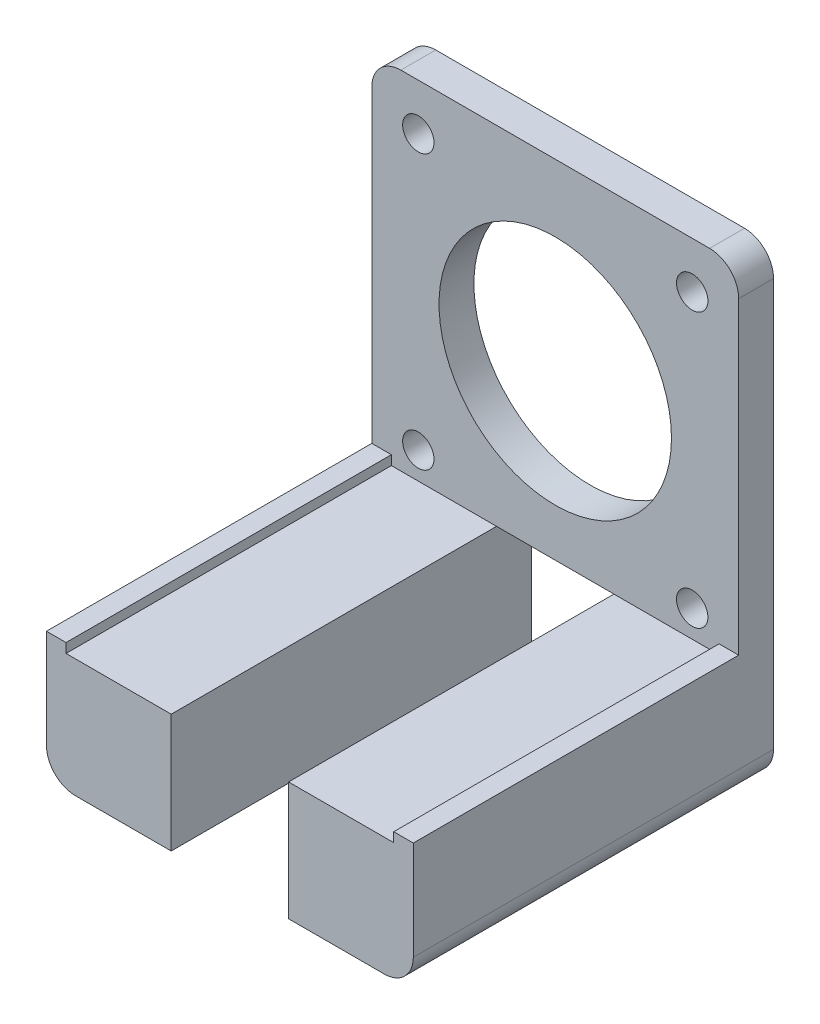
SolidWorks part; units mm, degrees
ref_plane "Alzado" through (0, 0, 0) normal (0, 0, 1) x (1, 0, 0)
ref_plane "Planta" through (0, 0, 0) normal (0, 1, 0) x (1, 0, 0)
ref_plane "Vista lateral" through (0, 0, 0) normal (1, 0, 0) x (0, 0, -1)
sketch "Croquis1" plane through (0, 0, 0) normal (0, 0, 1) x (1, 0, 0)
  line L0 (0, 0) -> (47.14, -47.14) construction
  line L1 (-8, -50.14) -> (-8, 3)
  line L2 (0, -47.14) -> (47.14, -47.14)
  line L3 (0, -47.14) -> (0, 0)
  line L4 (0, 0) -> (47.14, 0)
  line L5 (47.14, -47.14) -> (47.14, 0)
  line L6 (-3, 8) -> (50.14, 8)
  line L7 (55.14, -50.14) -> (55.14, 3)
  line L8 (-3, -55.14) -> (50.14, -55.14)
  line L9 (-8, -55.14) -> (-8, 8) construction
  line L10 (-8, -55.14) -> (55.14, -55.14) construction
  line L11 (55.14, -55.14) -> (55.14, 8) construction
  line L12 (-8, 8) -> (55.14, 8) construction
  circle A0 centre (0, 0) radius 2.7
  circle A1 centre (47.14, 0) radius 2.7
  circle A2 centre (47.14, -47.14) radius 2.7
  circle A3 centre (0, -47.14) radius 2.7
  circle A4 centre (23.57, -23.57) radius 20
  arc A5 (-8, -50.14) -> (-3, -55.14) centre (-3, -50.14) ccw
  arc A6 (55.14, -50.14) -> (50.14, -55.14) centre (50.14, -50.14) cw
  arc A7 (50.14, 8) -> (55.14, 3) centre (50.14, 3) cw
  arc A8 (-3, 8) -> (-8, 3) centre (-3, 3) ccw
  dimension "D1" = 5.4
  dimension "D4" = 40
  dimension "D6" = 5
  dimension "D5" = 8
  dimension "D2" = 2
  dimension "D3" = 2
extrude "Saliente-Extruir1" add sketch "Croquis1" along normal blind 6 contours L6 A8 L1 A5 L8 A6 L7 A7 A3 L3 A0 L4 A1 L5 A2 L2 | A3 L2 A2 L5 A1 L4 A0 L3 A4
sketch "Croquis2" plane through (0, 0, 6) normal (0, 0, 1) x (1, 0, 0)
  line L0 (55.14, -33.6563) -> (55.14, -55.14) construction
  line L1 (55.14, -50.14) -> (55.14, 3) construction
  line L2 (24.5636, -55.14) -> (55.14, -55.14) construction
  line L3 (-3, -55.14) -> (50.14, -55.14) construction
  line L4 (-4.63, -51.77) -> (-4.63, 4.63)
  line L5 (0, -47.14) -> (47.14, -47.14)
  line L6 (0, -47.14) -> (0, 0)
  line L7 (0, 0) -> (47.14, 0)
  line L8 (47.14, -47.14) -> (47.14, 0)
  line L9 (-4.63, 4.63) -> (51.77, 4.63)
  line L10 (51.77, -51.77) -> (51.77, 4.63)
  line L11 (-4.63, -51.77) -> (51.77, -51.77)
  line L12 (23.57, -47.14) -> (23.57, -96.2906) construction
  line L13 (13.47, -72.17) -> (13.47, -51.77)
  line L14 (-8, -50.14) -> (55.14, -50.14)
  line L15 (-8, -50.14) -> (-8, -67.17)
  line L16 (-3, -72.17) -> (50.14, -72.17)
  line L17 (55.14, -50.14) -> (55.14, -67.17)
  line L18 (33.67, -72.17) -> (33.67, -51.77)
  arc A0 (50.14, -72.17) -> (55.14, -67.17) centre (50.14, -67.17) ccw
  arc A1 (-8, -67.17) -> (-3, -72.17) centre (-3, -67.17) ccw
  arc M24 (-8, -50.14) -> (-3, -55.14) centre (-3, -50.14) ccw
  line M25 (-3, -55.14) -> (50.14, -55.14)
  arc M26 (50.14, -55.14) -> (55.14, -50.14) centre (50.14, -50.14) ccw
  dimension "D3" = 5
  dimension "D1" = 56.4
  dimension "D2" = 20.4
  dimension "D4" = 10.1
extrude "Saliente-Extruir2" add sketch "Croquis2" along normal blind 56 and the other way through all contours L15 A1 L16 L13 M25 M24 | L16 A0 L17 L18 M26 M25 | L14 L13 L11 L4 M24 M25 | L18 L14 L10 L11 M25 M26
sketch "Croquis3" plane through (0, 0, 62) normal (0, 0, 1) x (1, 0, 0)
  line L1 (13.47, -72.17) -> (33.67, -72.17)
  line L2 (13.47, -72.17) -> (13.47, -51.77)
  line L3 (13.47, -51.77) -> (33.67, -51.77)
  line L4 (33.67, -72.17) -> (33.67, -51.77)
extrude "Cortar-Extruir1" cut sketch "Croquis3" against normal through all
